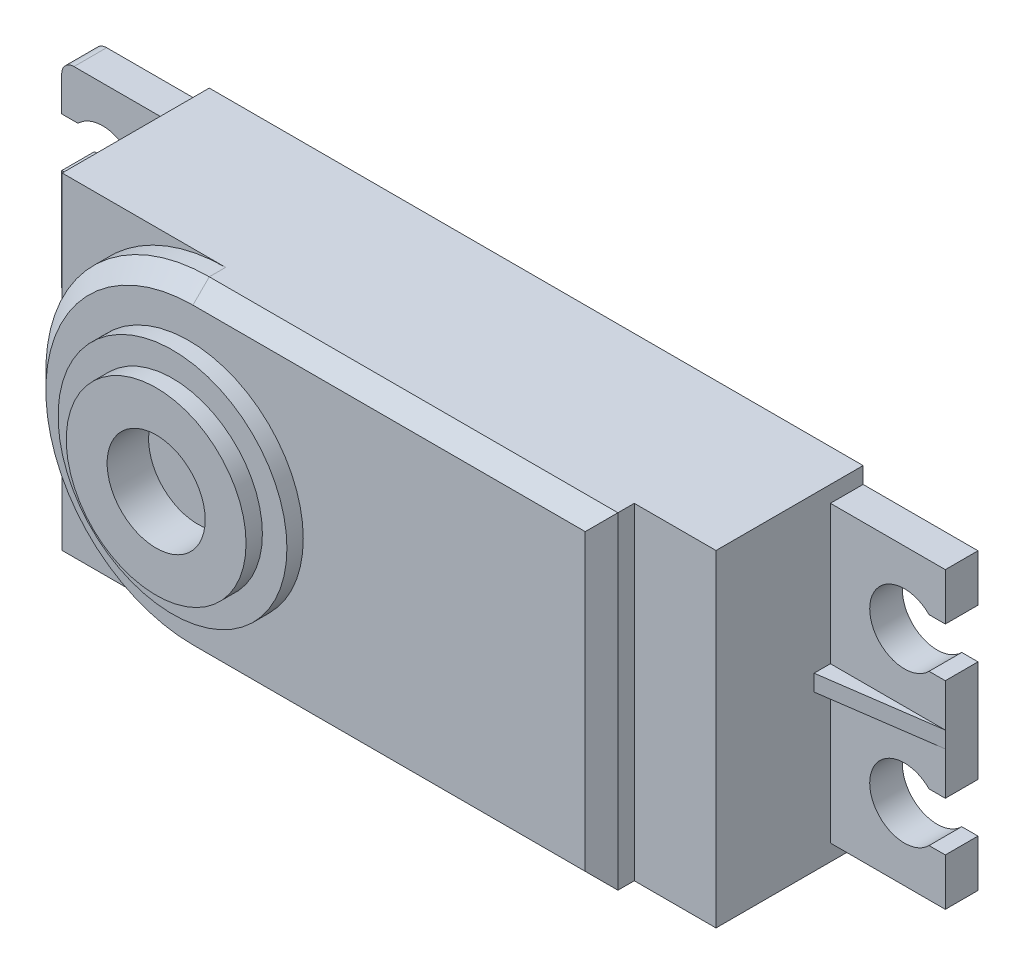
SolidWorks part; units mm, degrees
ref_plane "Front Plane" through (0, 0, 0) normal (0, 0, 1) x (1, 0, 0)
ref_plane "Top Plane" through (0, 0, 0) normal (0, 1, 0) x (1, 0, 0)
ref_plane "Right Plane" through (0, 0, 0) normal (1, 0, 0) x (0, 0, -1)
sketch "Sketch1" plane through (0, 0, 0) normal (0, 0, 1) x (1, 0, 0)
  line L1 (-20, -10) -> (20, -10)
  line L2 (-20, -10) -> (-20, 10)
  line L3 (-20, 10) -> (20, 10)
  line L4 (20, -10) -> (20, 10)
  line L5 (-20, -10) -> (20, 10) construction
  line L6 (-20, 10) -> (20, -10) construction
  point P0 (0, 0)
extrude "Boss-Extrude1" add sketch "Sketch1" along normal blind 9 contours L3 L4 L1 L2
sketch "Sketch2" plane through (0, 0, 9) normal (0, 0, 1) x (1, 0, 0)
  line L0 (-20, 10) -> (20, 10) construction
  line L1 (15, 10) -> (-10, 10)
  line L2 (15, 10) -> (15, -10)
  line L3 (15, -10) -> (-10, -10)
  line L5 (-20, -10) -> (20, -10) construction
  line L6 (-20, -10) -> (-20, 10) construction
  arc A0 (-10, 10) -> (-10, -10) centre (-10, 0) ccw
  dimension "D1" = 10
  dimension "D2" = 34.9999
extrude "Boss-Extrude2" add sketch "Sketch2" along normal blind 2
chamfer "Chamfer2" distance 1 angle 45 4 edges at (2.5, -10, 11) (-20, 0, 11) (2.5, 10, 11) (15, 0, 11)
sketch "Sketch3" plane through (0, 0, 11) normal (0, 0, 1) x (1, 0, 0)
  line L0 (-20, 0) -> (-20, 10) construction
  circle A0 centre (-10.25, 0) radius 7
  dimension "D1" = 14
  dimension "D2" = 9.75
extrude "Boss-Extrude3" add sketch "Sketch3" along normal blind 1
sketch "Sketch4" plane through (0, 0, 12) normal (0, 0, 1) x (1, 0, 0)
  circle A0 centre (-10.25, 0) radius 5.5
  dimension "D1" = 11
extrude "Boss-Extrude4" add sketch "Sketch4" along normal blind 1
sketch "Sketch5" plane through (0, 0, 13) normal (0, 0, 1) x (1, 0, 0)
  circle A0 centre (-10.25, 0) radius 3
  dimension "D1" = 6
extrude "Cut-Extrude1" cut sketch "Sketch5" against normal blind 2.54
sketch "Sketch6" plane through (0, 0, 0) normal (0, 0, -1) x (-1, 0, 0)
  line L0 (20, -10) -> (20, 10) construction
  line L1 (20, 9) -> (27.0279, 9)
  line L2 (20, 9) -> (20, -9)
  line L3 (20, -9) -> (27.0279, -9)
  line L4 (27.0279, 9) -> (27.0279, 6.1156)
  line L5 (20, 10) -> (-20, 10) construction
  line L10 (26.0332, 6.1156) -> (27.0279, 6.1156)
  line L11 (27.0279, 3.1156) -> (26.0332, 3.1156)
  line L12 (27.0279, -3.1156) -> (26.0332, -3.1156)
  line L13 (27.0279, -6.1156) -> (26.0332, -6.1156)
  line L14 (27.0279, 3.1156) -> (27.0279, -3.1156)
  line L15 (27.0279, -6.1156) -> (27.0279, -9)
  arc A4 (26.0332, 6.1156) -> (26.0332, 3.1156) centre (24.528, 4.6156) ccw
  arc A5 (26.0332, -3.1156) -> (26.0332, -6.1156) centre (24.528, -4.6156) ccw
  point P6 (27.0279, 0)
  point P27 (26.0332, 3.1156)
  point P28 (26.0332, 6.1156)
  point P29 (26.0332, -6.1156)
  dimension "D1" = 7.0279
  dimension "D2" = 1
extrude "Boss-Extrude5" add sketch "Sketch6" against normal blind 2
fillet "Fillet1" radius 0.75 2 edges at (-27.0279, -9, 1) (-27.0279, 9, 1)
sketch "Sketch7" plane through (0, 0, 0) normal (0, 1, 0) x (1, 0, 0)
  line L0 (-27.0279, -2) -> (-20, -3)
  line L1 (-20, -9) -> (-20, 0) construction
  line L2 (-20, -3) -> (-20, -2)
  line L3 (-20, -2) -> (-27.0279, -2)
  dimension "D1" = 1
extrude "Boss-Extrude6" add sketch "Sketch7" along normal mid plane 1
mirror "Mirror1" about plane through (0, 0, 0) normal (1, 0, 0) of "Boss-Extrude6", "Boss-Extrude5"
